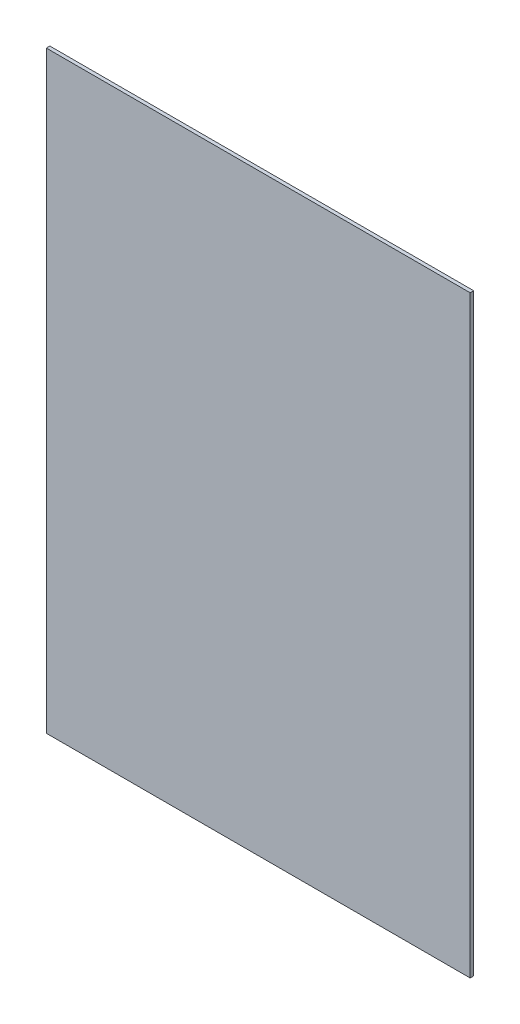
SolidWorks part; units mm, degrees
material "Glass"
ref_plane "Front Plane" through (0, 0, 0) normal (0, 0, 1) x (1, 0, 0)
ref_plane "Top Plane" through (0, 0, 0) normal (0, 1, 0) x (1, 0, 0)
ref_plane "Right Plane" through (0, 0, 0) normal (1, 0, 0) x (0, 0, -1)
sketch "Sketch1" plane through (0, 0, 0) normal (0, 0, 1) x (1, 0, 0)
  line L1 (0, 0) -> (381, 0)
  line L2 (0, 0) -> (0, 533.4)
  line L3 (0, 533.4) -> (381, 533.4)
  line L4 (381, 0) -> (381, 533.4)
  dimension "D1" = 381
  dimension "D2" = 533.4
  dimension "D3" = 533.4
extrude "Boss-Extrude1" add sketch "Sketch1" along normal blind 3.175
